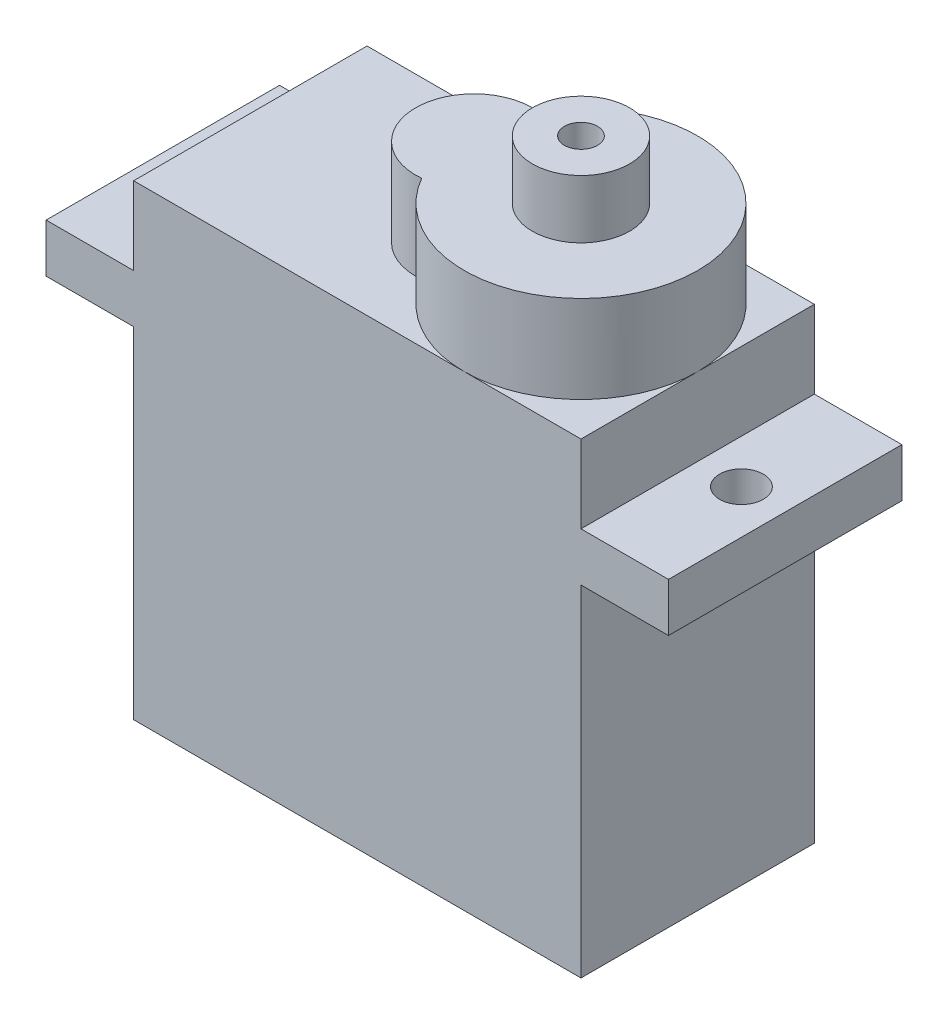
SolidWorks part; units mm, degrees
ref_plane "Front Plane" through (0, 0, 0) normal (0, 0, 1) x (1, 0, 0)
ref_plane "Top Plane" through (0, 0, 0) normal (0, 1, 0) x (1, 0, 0)
ref_plane "Right Plane" through (0, 0, 0) normal (1, 0, 0) x (0, 0, -1)
sketch "Sketch1" plane through (0, 0, 0) normal (0, 1, 0) x (1, 0, 0)
  line L1 (11.5, -6) -> (-11.5, -6)
  line L2 (11.5, -6) -> (11.5, 6)
  line L3 (11.5, 6) -> (-11.5, 6)
  line L4 (-11.5, -6) -> (-11.5, 6)
  line L5 (11.5, -6) -> (-11.5, 6) construction
  line L6 (11.5, 6) -> (-11.5, -6) construction
  point P0 (0, 0)
  dimension "D1" = 23
  dimension "D2" = 12
extrude "Boss-Extrude1" add sketch "Sketch1" along normal blind 24
sketch "Sketch2" plane through (0, 24, 0) normal (0, 1, 0) x (1, 0, 0)
  line L1 (11.5, 6) -> (-11.5, 6) construction
  line L3 (11.5, -6) -> (11.5, 6) construction
  line L4 (0, 0) -> (11.5, 0) construction
  arc A0 (0.2955, 2.9854) -> (0.2955, -2.9854) centre (0, 0) ccw
  arc A1 (0.2955, -2.9854) -> (0.2955, 2.9854) centre (5.5, 0) ccw
  dimension "D2" = 6
extrude "Boss-Extrude2" add sketch "Sketch2" along normal blind 4.5
sketch "Sketch3" plane through (0, 28.5, 0) normal (0, 1, 0) x (1, 0, 0)
  circle A0 centre (5.5, 0) radius 2.5
  dimension "D1" = 5
extrude "Boss-Extrude3" add sketch "Sketch3" along normal blind 3
sketch "Sketch4" plane through (0, 31.5, 0) normal (0, 1, 0) x (1, 0, 0)
  circle A0 centre (5.5, 0) radius 0.85
  dimension "D1" = 1.7
extrude "Cut-Extrude1" cut sketch "Sketch4" against normal blind 5
sketch "Sketch5" plane through (0, 24, 0) normal (0, 1, 0) x (1, 0, 0)
  line L0 (-11.5, -6) -> (5.5, -6) construction
  line L1 (-11.5, 6) -> (-16, 6)
  line L2 (-11.5, 6) -> (-11.5, -6)
  line L3 (-11.5, -6) -> (-16, -6)
  line L4 (-16, 6) -> (-16, -6)
  line L5 (-16, 0) -> (-11.5, 0) construction
  line L6 (0, 0) -> (0, -8.1133) construction
  line L7 (16, 0) -> (11.5, 0) construction
  line L8 (16, 6) -> (16, -6)
  line L9 (11.5, -6) -> (16, -6)
  line L10 (11.5, 6) -> (11.5, -6)
  line L11 (11.5, 6) -> (16, 6)
  circle A0 centre (-13.75, 0) radius 1.125
  circle A1 centre (13.75, 0) radius 1.125
  dimension "D2" = 2.25
  dimension "D1" = 4.5
extrude "Boss-Extrude6" add sketch "Sketch5" against normal blind 2.5 from offset 4
